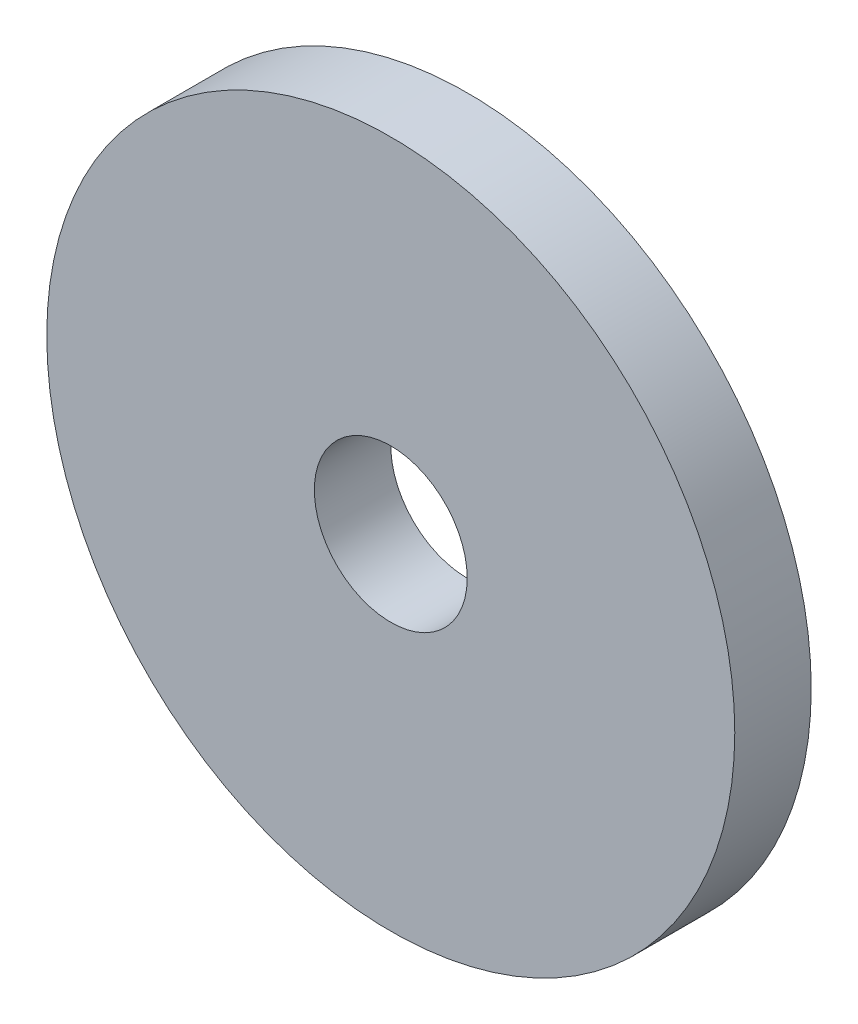
SolidWorks part; units mm, degrees
ref_plane "Plan1" through (0, 0, 0) normal (0, 0, 1) x (1, 0, 0)
ref_plane "Plan2" through (0, 0, 0) normal (0, 1, 0) x (1, 0, 0)
ref_plane "Plan3" through (0, 0, 0) normal (1, 0, 0) x (0, 0, -1)
sketch "Esquisse1" plane through (0, 0, 0) normal (0, 0, 1) x (1, 0, 0)
  circle A0 centre (0, 0) radius 18
  circle A1 centre (0, 0) radius 4
  dimension "D1" = 36
  dimension "D2" = 8
extrude "Base-Extrusion" add sketch "Esquisse1" along normal blind 4
